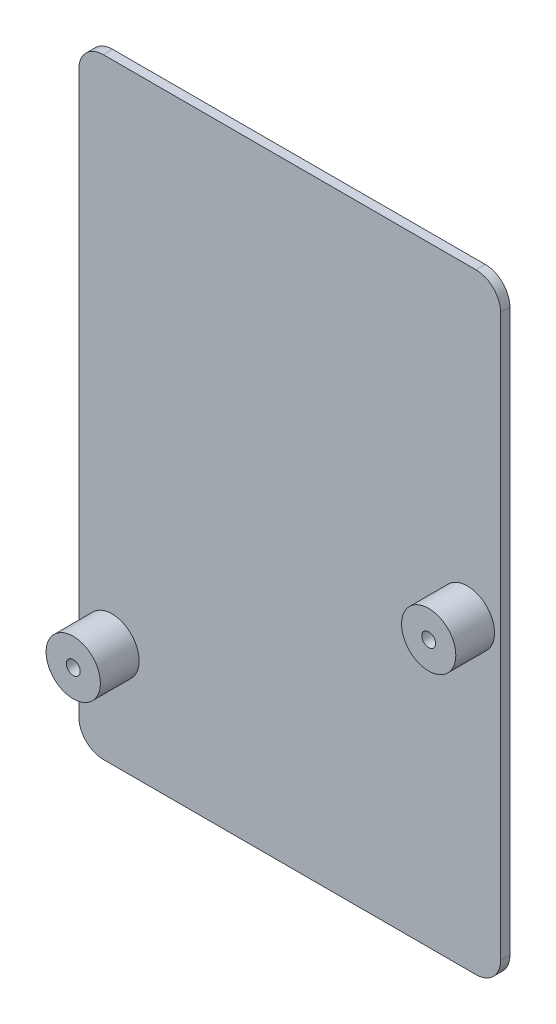
SolidWorks part; units mm, degrees
ref_plane "Front Plane" through (0, 0, 0) normal (0, 0, 1) x (1, 0, 0)
ref_plane "Top Plane" through (0, 0, 0) normal (0, 1, 0) x (1, 0, 0)
ref_plane "Right Plane" through (0, 0, 0) normal (1, 0, 0) x (0, 0, -1)
sketch "Sketch1" plane through (0, 0, 0) normal (0, 0, 1) x (1, 0, 0)
  line L1 (-27.2034, -39.37) -> (27.2034, -39.37)
  line L2 (-27.2034, -39.37) -> (-27.2034, 39.37)
  line L3 (-27.2034, 39.37) -> (27.2034, 39.37)
  line L4 (27.2034, -39.37) -> (27.2034, 39.37)
  line L5 (-27.2034, -39.37) -> (27.2034, 39.37) construction
  line L6 (-27.2034, 39.37) -> (27.2034, -39.37) construction
  point P0 (0, 0)
  dimension "D1" = 78.74
  dimension "D2" = 54.4068
extrude "Boss-Extrude1" add sketch "Sketch1" along normal blind 1.2
fillet "Fillet1" radius 3.175 4 edges at (-27.2034, 39.37, 0.6) (-27.2034, -39.37, 0.6) (27.2034, -39.37, 0.6) (27.2034, 39.37, 0.6)
sketch "Sketch3" plane through (0, 0, 1.2) normal (0, 0, 1) x (1, 0, 0)
  line L0 (-27.2034, 0) -> (27.2034, 0) construction
  line L1 (-27.2034, 36.195) -> (-27.2034, -36.195) construction
  line L2 (27.2034, -36.195) -> (27.2034, 36.195) construction
  line L3 (0, 39.37) -> (0, -39.37) construction
  line L4 (24.0284, 39.37) -> (-24.0284, 39.37) construction
  line L5 (-24.0284, -39.37) -> (24.0284, -39.37) construction
  circle A0 centre (-50, 0) radius 2
  circle A1 centre (50, 0) radius 2
  dimension "D1" = 4
  dimension "D2" = 50
extrude "Cut-Extrude2" [suppressed] cut sketch "Sketch3" against normal up to next
sketch "Sketch2" plane through (0, 0, 1.2) normal (0, 0, 1) x (1, 0, 0)
  line L0 (-27.2034, 0) -> (27.2034, 0) construction
  line L1 (-27.2034, 36.195) -> (-27.2034, -36.195) construction
  line L2 (27.2034, -36.195) -> (27.2034, 36.195) construction
  line L3 (0, -39.37) -> (0, 39.37) construction
  line L4 (24.0284, 39.37) -> (-24.0284, 39.37) construction
  line L5 (-24.0284, -39.37) -> (24.0284, -39.37) construction
  line L6 (-22.925, 39.37) -> (-22.925, -39.37) construction
  circle A0 centre (-22.925, -26.04) radius 0.89
  circle A1 centre (22.925, 0) radius 0.89
  dimension "D1" = 1.78
  dimension "D2" = 1.78
  dimension "D4" = 0
  dimension "D5" = 26.04
  dimension "D6" = 45.85
  dimension "D3" = 22.925
extrude "Cut-Extrude1" cut sketch "Sketch2" against normal up to next and the other way through all
sketch "Sketch4" plane through (0, 0, 1.2) normal (0, 0, 1) x (1, 0, 0)
  circle A0 centre (-22.925, -26.04) radius 3.5
  circle A1 centre (22.925, 0) radius 3.5
  circle A9 centre (-22.925, -26.04) radius 0.89
  circle A10 centre (22.925, 0) radius 0.89
  dimension "D1" = 7
  dimension "D2" = 7
  dimension "D3" = 1.78
  dimension "D4" = 1.78
extrude "Boss-Extrude2" add sketch "Sketch4" along normal blind 5
equation "\"Box_Width\" = 79.93mm"
equation "\"Box_Length\" = 129.93mm"
equation "\"LoggerMount_Width\" = 26.04mm"
equation "\"LoggerMount_Length\" = 45.85mm"
equation "\"LoggerMount_Hole\"= 2.5mm"
equation "\"Box_Hole\"= 4mm"
equation "\"D1@Sketch1\"=3.1in"
equation "\"D2@Sketch1\"=(4.284in/2)"
equation "\"D5@Sketch2\"= \"LoggerMount_Width\""
equation "\"D1@Sketch3\"=\"Box_Hole\""
equation "\"Box_HoleSpacing\"= 100mm"
equation "\"D2@Sketch3\"= \"Box_HoleSpacing\"/2"
equation "\"D6@Sketch2\"=\"LoggerMount_Length\""
equation "\"D3@Sketch2\"=\"LoggerMount_Length\"/2"
